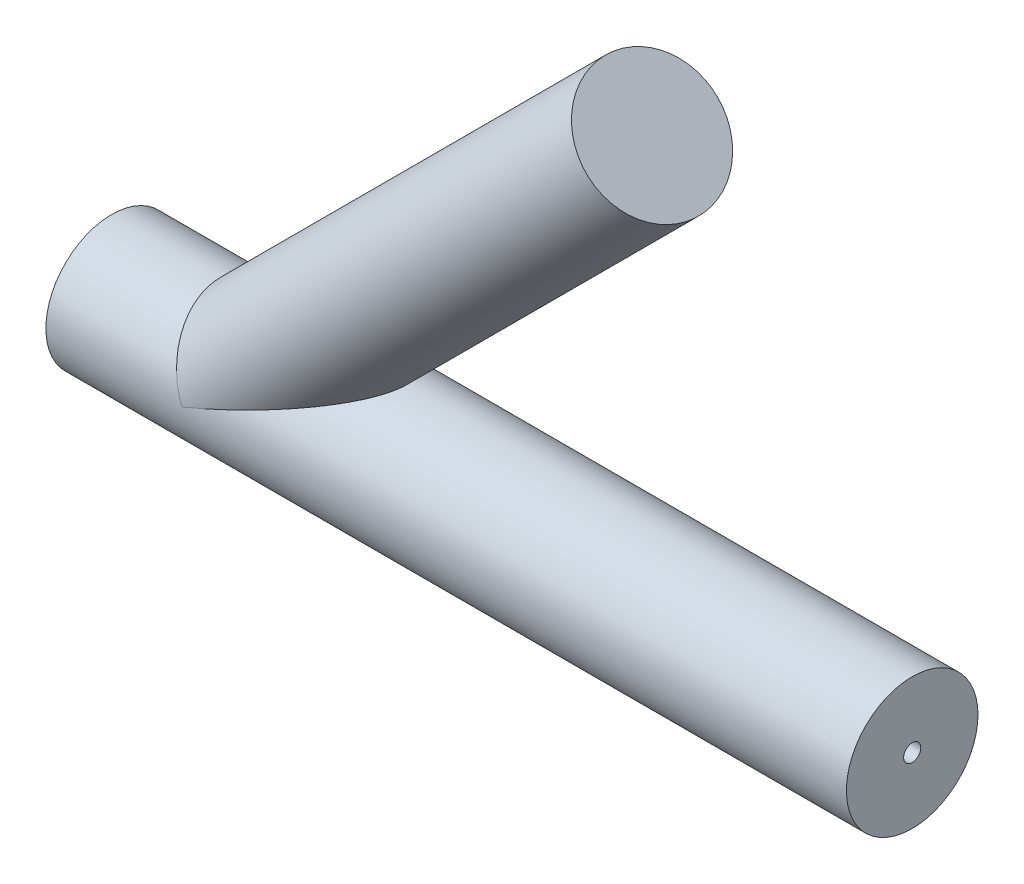
SolidWorks part; units mm, degrees
ref_plane "Front Plane" through (0, 0, 0) normal (0, 0, 1) x (1, 0, 0)
ref_plane "Top Plane" through (0, 0, 0) normal (0, 1, 0) x (1, 0, 0)
ref_plane "Right Plane" through (0, 0, 0) normal (1, 0, 0) x (0, 0, -1)
sketch "Sketch1" plane through (0, 0, 0) normal (1, 0, 0) x (0, 0, -1)
  circle A0 centre (0, 0) radius 28.194
  dimension "D1" = 56.388
extrude "Boss-Extrude1" add sketch "Sketch1" along normal blind 343
sketch "Sketch4" plane through (0, 0, 0) normal (0, 1, 0) x (1, 0, 0)
  line L0 (58.3, -34.1123) -> (58.3, 43.0803)
  line L1 (0, 28.194) -> (0, -28.194) construction
  circle A0 centre (58.3, 0) radius 15
  dimension "D1" = 58.3
ref_plane "Plane1" through (29.15, 29.15, 0) normal (0.7071, 0.7071, 0) x (0.7071, -0.7071, 0)
sketch "Sketch5" plane through (29.15, 29.15, 0) normal (0.7071, 0.7071, 0) x (0.7071, -0.7071, 0)
  circle A0 centre (41.2243, 0) radius 28.194
  dimension "D1" = 56.388
extrude "Boss-Extrude3" add sketch "Sketch5" along normal blind 245 contours A0
sketch "Sketch7" plane through (0, 0, 0) normal (-1, 0, 0) x (0, 0, 1)
  circle A0 centre (0, 0) radius 3.675
  dimension "D1" = 7.35
extrude "Cut-Extrude1" cut sketch "Sketch7" against normal blind 369.4
